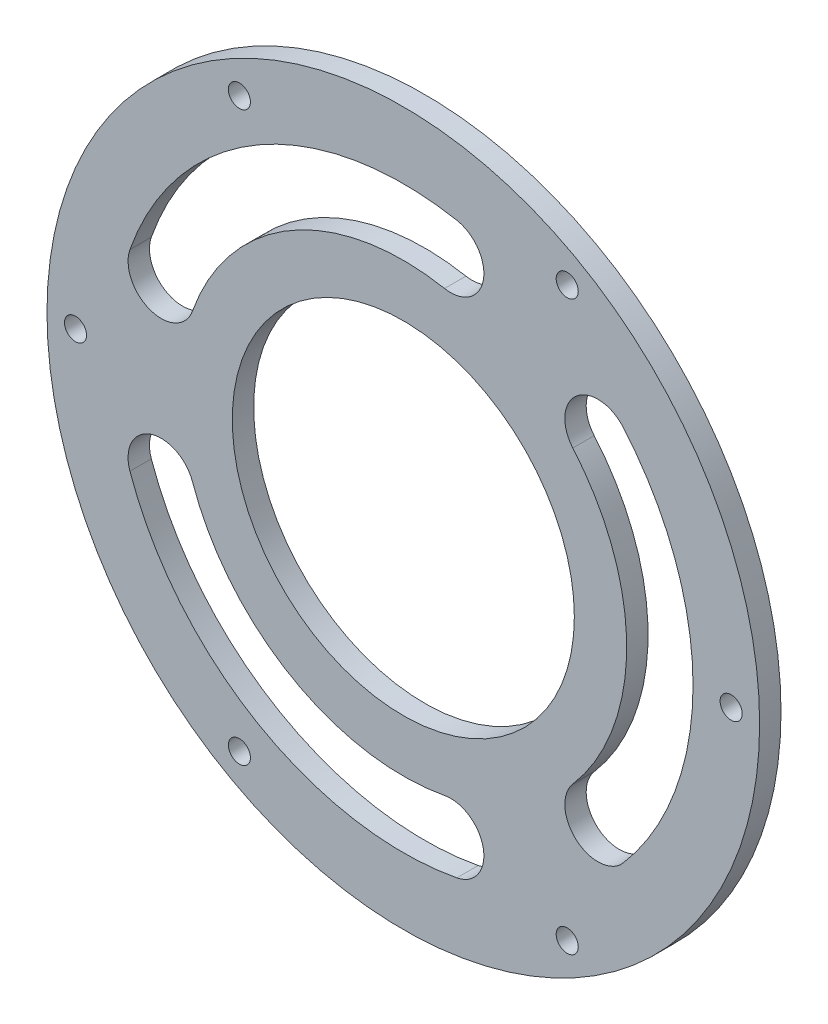
SolidWorks part; units mm, degrees
ref_plane "前视基准面" through (0, 0, 0) normal (0, 0, 1) x (1, 0, 0)
ref_plane "上视基准面" through (0, 0, 0) normal (0, 1, 0) x (1, 0, 0)
ref_plane "右视基准面" through (0, 0, 0) normal (1, 0, 0) x (0, 0, -1)
other "Configuration Table"
sketch "草图1" plane through (0, 0, 0) normal (0, 0, 1) x (1, 0, 0)
  line L0 (42, 0) -> (50, 0) construction
  line L1 (50, 0) -> (52, 0) construction
  line L2 (0, 0) -> (0, 42) construction
  line L7 (40, 0) -> (42, 0) construction
  circle A0 centre (0, 0) radius 50 construction
  circle A1 centre (0, 0) radius 42 construction
  circle A2 centre (46, 0) radius 1.55
  circle A3 centre (23, -39.8372) radius 1.55
  circle A4 centre (-23, -39.8372) radius 1.55
  circle A5 centre (-46, 0) radius 1.55
  circle A6 centre (-23, 39.8372) radius 1.55
  circle A7 centre (23, 39.8372) radius 1.55
  circle A8 centre (0, 0) radius 52
  circle A22 centre (0, 0) radius 40
  point P20 (0, 0)
  point P38 (0, 0)
  point P58 (0, 0)
  dimension "D1" = 100
  dimension "D2" = 8
  dimension "D3" = 3.1
  dimension "D4" = 6
  dimension "D10" = 6
  dimension "D5" = 2
extrude "凸台-拉伸1" add sketch "草图1" along normal blind 3
sketch "草图2" plane through (0, 0, 3) normal (0, 0, 1) x (1, 0, 0)
  circle A0 centre (0, 0) radius 40
  circle A1 centre (0, 0) radius 24
  dimension "D1" = 80
  dimension "D2" = 48
extrude "凸台-拉伸2" add sketch "草图2" against normal blind 3
sketch "草图4" plane through (0, 0, 0) normal (0, 0, -1) x (-1, 0, 0)
  line L0 (0, 0) -> (29.5753, 10.388) construction
  line L1 (23, 39.8372) -> (0, 0) construction
  arc A0 (-6.6511, 35.3803) -> (33.9658, 11.9301) centre (0, 0) cw construction
  arc A1 (38.3562, 13.4722) -> (-7.5108, 39.9535) centre (0, 0) ccw
  arc A2 (29.5753, 10.388) -> (-5.7914, 30.807) centre (0, 0) ccw
  arc A3 (29.5753, 10.388) -> (38.3562, 13.4722) centre (33.9658, 11.9301) ccw
  arc A4 (-7.5108, 39.9535) -> (-5.7914, 30.807) centre (-6.6511, 35.3803) ccw
  circle A5 centre (0, 0) radius 52 construction
  arc A6 (-5.7914, -30.807) -> (29.5753, -10.388) centre (0, 0) ccw
  arc A7 (-5.7914, -30.807) -> (-7.5108, -39.9535) centre (-6.6511, -35.3803) ccw
  arc A8 (38.3562, -13.4722) -> (29.5753, -10.388) centre (33.9658, -11.9301) ccw
  arc A9 (-7.5108, -39.9535) -> (38.3562, -13.4722) centre (0, 0) ccw
  arc A10 (33.9658, -11.9301) -> (-6.6511, -35.3803) centre (0, 0) cw construction
  arc A11 (-23.7839, 20.419) -> (-23.7839, -20.419) centre (0, 0) ccw
  arc A12 (-23.7839, 20.419) -> (-30.8454, 26.4813) centre (-27.3147, 23.4501) ccw
  arc A13 (-30.8454, -26.4813) -> (-23.7839, -20.419) centre (-27.3147, -23.4501) ccw
  arc A14 (-30.8454, 26.4813) -> (-30.8454, -26.4813) centre (0, 0) ccw
  arc A15 (-27.3147, -23.4501) -> (-27.3147, 23.4501) centre (0, 0) cw construction
  circle A16 centre (23, 39.8372) radius 2.6279 construction
  point P3 (18, 31.1769)
  point P13 (18, -31.1769)
  point P22 (-36, 0)
  dimension "D1" = 36
  dimension "D2" = 3
extrude "切除-拉伸1" cut sketch "草图4" against normal blind 10
sketch "草图5" plane through (0, 0, 0) normal (0, 0, -1) x (-1, 0, 0)
  circle A0 centre (0, 0) radius 50
  circle A1 centre (0, 0) radius 63.0241
  dimension "D1" = 100
extrude "切除-拉伸2" cut sketch "草图5" against normal blind 10
